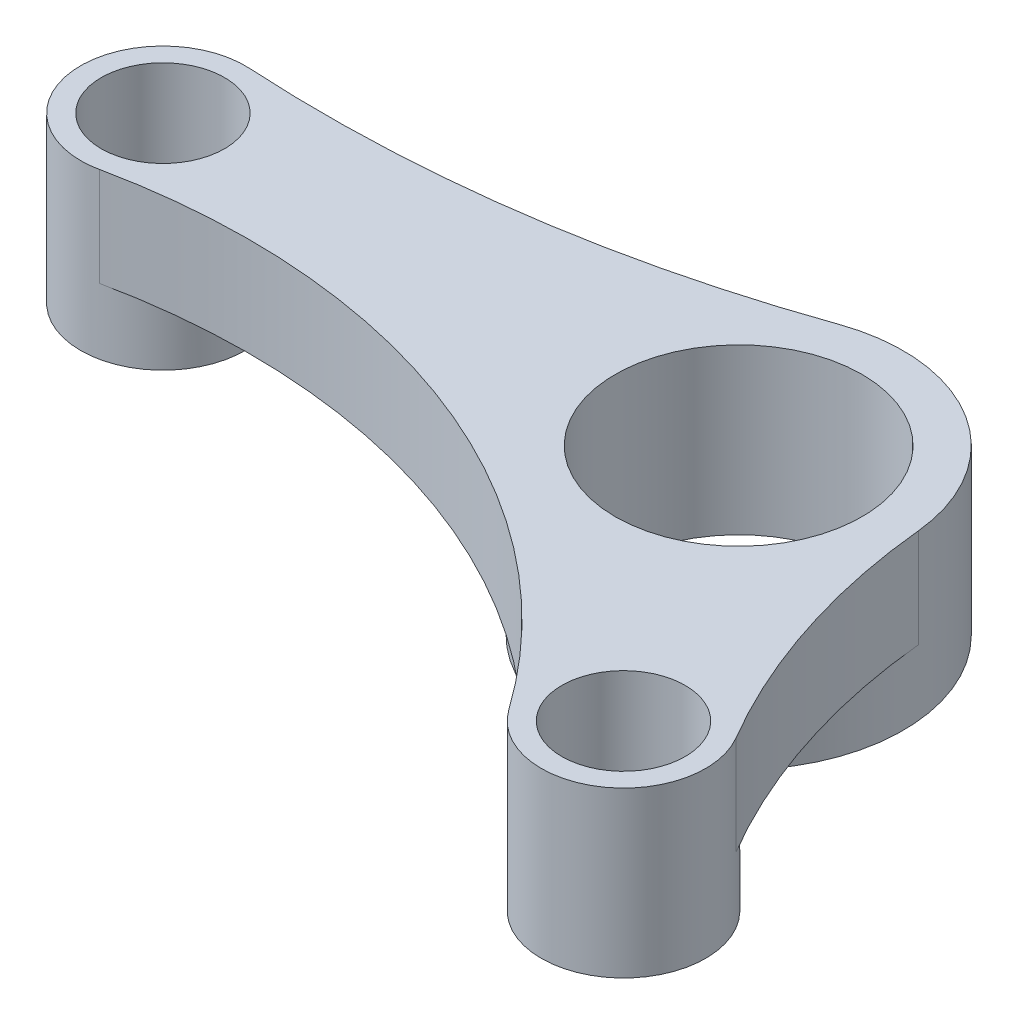
SolidWorks part; units mm, degrees
ref_plane "Front Plane" through (0, 0, 0) normal (0, 0, 1) x (1, 0, 0)
ref_plane "Top Plane" through (0, 0, 0) normal (0, 1, 0) x (1, 0, 0)
ref_plane "Right Plane" through (0, 0, 0) normal (1, 0, 0) x (0, 0, -1)
sketch "Sketch1" plane through (0, 0, 0) normal (0, 1, 0) x (1, 0, 0)
  circle A0 centre (0, 0) radius 20
  circle A1 centre (-70, 0) radius 10
  circle A2 centre (22, -36) radius 10
  circle A3 centre (-70, 0) radius 7.5
  circle A4 centre (0, 0) radius 15
  circle A5 centre (22, -36) radius 7.5
  dimension "D1" = 40
  dimension "D2" = 20
  dimension "D3" = 20
  dimension "D7" = 30
  dimension "D8" = 15
  dimension "D9" = 15
  dimension "D4" = 22
  dimension "D5" = 70
  dimension "D6" = 36
extrude "Boss-Extrude1" add sketch "Sketch1" along normal blind 20
sketch "Sketch3" plane through (0, 20, 0) normal (0, 1, 0) x (1, 0, 0)
  circle A0 centre (-70, 0) radius 10 construction
  circle A1 centre (22, -36) radius 10 construction
  circle A2 centre (0, 0) radius 20 construction
  arc A3 (-69.4118, 9.9827) -> (-67.935, -9.7845) centre (-70, 0) ccw
  arc A4 (13.8428, -41.7845) -> (30.6142, -30.921) centre (22, -36) ccw
  arc A5 (19.9055, 1.9422) -> (-6.6667, 18.8562) centre (0, 0) ccw
  arc A6 (-69.4118, 9.9827) -> (-6.6667, 18.8562) centre (-60, 169.7056) ccw
  arc A7 (13.8428, -41.7845) -> (-67.935, -9.7845) centre (-51.4148, -88.0602) ccw
  arc A8 (19.9055, 1.9422) -> (30.6142, -30.921) centre (99.5274, 9.7112) ccw
  circle A9 centre (22, -36) radius 7.5 construction
  circle A10 centre (0, 0) radius 15 construction
  circle A11 centre (-70, 0) radius 7.5 construction
  circle A12 centre (22, -36) radius 7.5
  circle A13 centre (0, 0) radius 15
  circle A14 centre (-70, 0) radius 7.5
  dimension "D1" = 160
  dimension "D2" = 160
  dimension "D3" = 160
extrude "Boss-Extrude2" add sketch "Sketch3" against normal blind 12
sketch "Sketch7" plane through (0, 0, 0) normal (0, -1, 0) x (1, 0, 0)
  arc A2 (-68.5545, 6.8491) -> (16.29, 40.0491) centre (-51.4148, 88.0602) ccw
  arc A3 (-61.7914, 5.7114) -> (-14.5955, 13.6738) centre (-51.4148, 88.0602) ccw
  arc A12 (-5.6667, -16.0278) -> (-69.5882, -6.9879) centre (-60, -169.7056) ccw
  arc A13 (-15.2174, -12.9781) -> (-62.6003, -6.7264) centre (-60, -169.7056) ccw
  arc A14 (13.8428, 41.7845) -> (30.6142, 30.921) centre (22, 36) ccw construction
  arc A15 (28.0299, 32.4447) -> (16.9196, -1.6509) centre (99.5274, -9.7112) ccw
  arc A16 (24.7937, 26.3982) -> (18.4026, 7.8323) centre (99.5274, -9.7112) ccw
  arc A17 (19.9055, -1.9422) -> (-6.6667, -18.8562) centre (0, 0) ccw construction
  circle A18 centre (-70, 0) radius 10 construction
  arc A19 (12.0952, 34.6235) -> (24.7937, 26.3982) centre (22, 36) ccw
  arc A20 (18.4026, 7.8323) -> (-4.7336, 19.4318) centre (0, 0) ccw
  arc A21 (-62.6003, -6.7264) -> (-61.7914, 5.7114) centre (-70, 0) ccw
  arc A22 (-14.5955, 13.6738) -> (-15.2174, -12.9781) centre (0, 0) ccw
  arc A23 (-4.7336, 19.4318) -> (12.0952, 34.6235) centre (-51.4148, 88.0602) ccw
  dimension "D1" = 3
  dimension "D2" = 3
  dimension "D3" = 3
extrude "Cut-Extrude3" cut sketch "Sketch7" against normal blind 12
